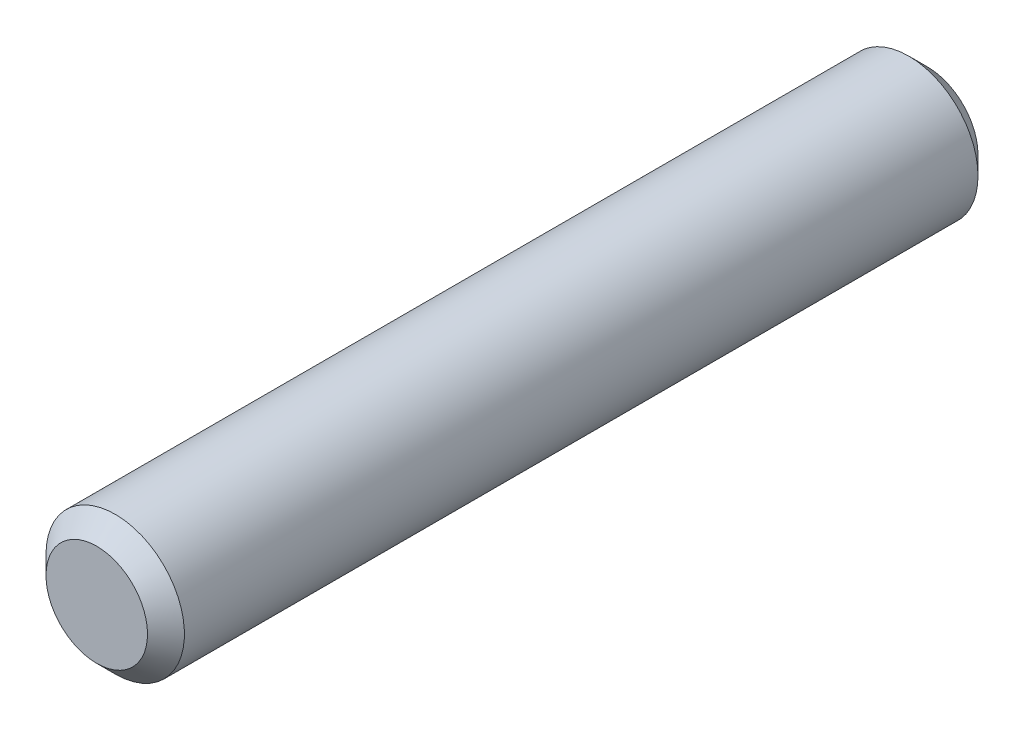
SolidWorks part; units mm, degrees
ref_plane "Front Plane" through (0, 0, 0) normal (0, 0, 1) x (1, 0, 0)
ref_plane "Top Plane" through (0, 0, 0) normal (0, 1, 0) x (1, 0, 0)
ref_plane "Right Plane" through (0, 0, 0) normal (1, 0, 0) x (0, 0, -1)
sketch "Sketch1" plane through (0, 0, 0) normal (0, 0, 1) x (1, 0, 0)
  circle A0 centre (0, 0) radius 7.5
  dimension "D1" = 15
extrude "Boss-Extrude1" add sketch "Sketch1" along normal blind 90
chamfer "Chamfer1" distance 2 angle 45 2 edges at (7.5, 0, 90) (7.5, 0, 0)
